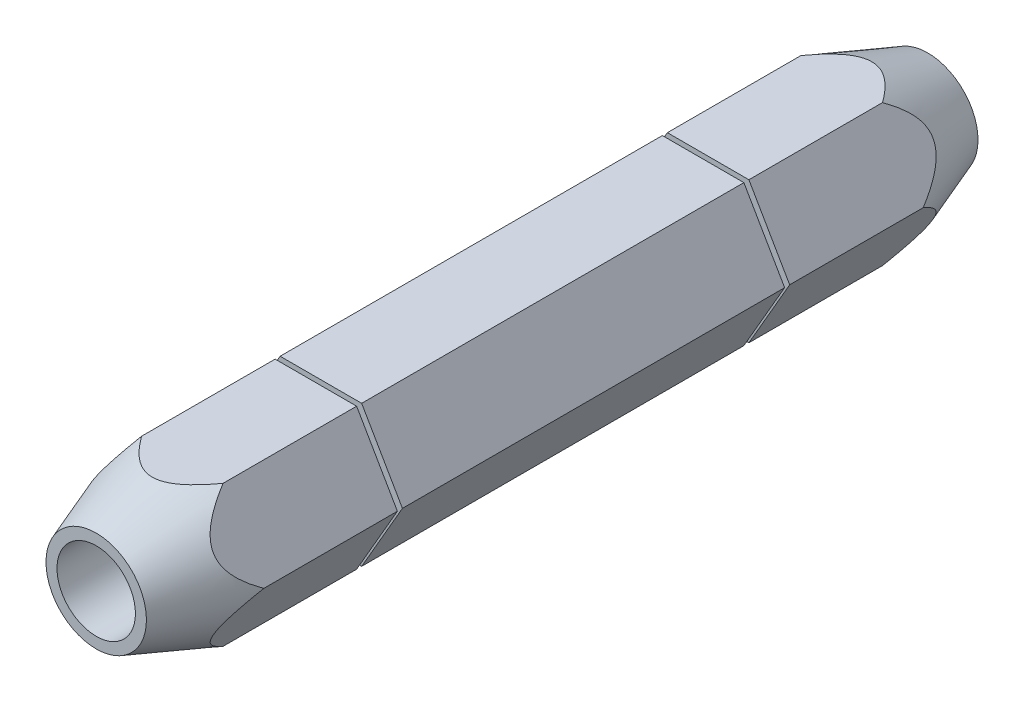
SolidWorks part; units mm, degrees
material "6061 Alloy"
ref_plane "front" through (0, 0, 0) normal (0, 0, 1) x (1, 0, 0)
ref_plane "top" through (0, 0, 0) normal (0, 1, 0) x (1, 0, 0)
ref_plane "right" through (0, 0, 0) normal (1, 0, 0) x (0, 0, -1)
sketch "Sketch1" plane through (0, 0, 0) normal (0, 0, 1) x (1, 0, 0)
  line L1 (8.2489, 0) -> (4.1244, 7.1437)
  line L2 (4.1244, 7.1437) -> (-4.1244, 7.1437)
  line L3 (-4.1244, 7.1437) -> (-8.2489, 0)
  line L4 (-8.2489, 0) -> (-4.1244, -7.1438)
  line L5 (-4.1244, -7.1438) -> (4.1244, -7.1438)
  line L6 (4.1244, -7.1438) -> (8.2489, 0)
  circle A0 centre (0, 0) radius 7.1438 construction
  dimension "D1" = 14.2875
extrude "Base-Extrude" add sketch "Sketch1" along normal mid plane 84.1375
sketch "Sketch2" plane through (0, 0, 0) normal (1, 0, 0) x (0, 0, -1)
  line L0 (-64.542, 0) -> (1.5962, 0) construction
  line L1 (42.0688, 0) -> (42.0688, 7.1437) construction
  line L2 (19.8438, 6.35) -> (19.3358, 6.35)
  line L3 (19.8438, 6.35) -> (19.8438, 8.89)
  line L4 (19.3358, 8.89) -> (-19.3358, 8.89)
  line L5 (19.3358, 6.35) -> (19.3358, 8.89)
  line L6 (-19.8438, 6.35) -> (-19.3358, 6.35)
  line L7 (-19.8438, 6.35) -> (-19.8438, 8.89)
  line L8 (-19.8438, 8.89) -> (-31.6009, 8.89)
  line L9 (-19.3358, 6.35) -> (-19.3358, 8.89)
  line L10 (-42.0688, 0) -> (-42.0688, 7.1437) construction
  line L11 (42.0688, 5.08) -> (42.0688, 18.082)
  line L12 (42.0688, 5.08) -> (31.6009, 8.89)
  line L13 (31.6009, 8.89) -> (19.8438, 8.89)
  line L14 (-31.6009, 8.89) -> (-42.0688, 5.08)
  line L15 (42.0688, 18.082) -> (-42.0688, 18.082)
  line L16 (-42.0688, 5.08) -> (-42.0688, 18.082)
  dimension "D1" = 12.7
  dimension "D2" = 22.225
  dimension "D3" = 22.225
  dimension "D4" = 12.7
  dimension "D5" = 0.508
  dimension "D6" = 0.508
  dimension "D7" = 10.16
  dimension "D8" = 10.16
  dimension "D9" = 20
  dimension "D10" = 20
  dimension "D11" = 17.78
revolve "Cut-Revolve1" cut sketch "Sketch2" angle 360 about L0
sketch "Sketch3" plane through (0, 0, 42.0688) normal (0, 0, 1) x (1, 0, 0)
  circle A0 centre (0, 0) radius 3.9688
  dimension "D1" = 7.9375
extrude "Cut-Extrude1" cut sketch "Sketch3" against normal through all
sketch "Sketch5" plane through (0, 7.1437, 0) normal (0, 1, 0) x (1, 0, 0)
  line L0 (2.2194, -19.3358) -> (2.2194, 19.3357) construction
  line L1 (4.1244, -19.3358) -> (-4.1244, -19.3358) construction
  line L2 (-4.1244, 19.3357) -> (4.1244, 19.3357) construction
  line L3 (4.1244, -19.3358) -> (4.1244, 19.3357) construction
  dimension "D1" = 1.905
